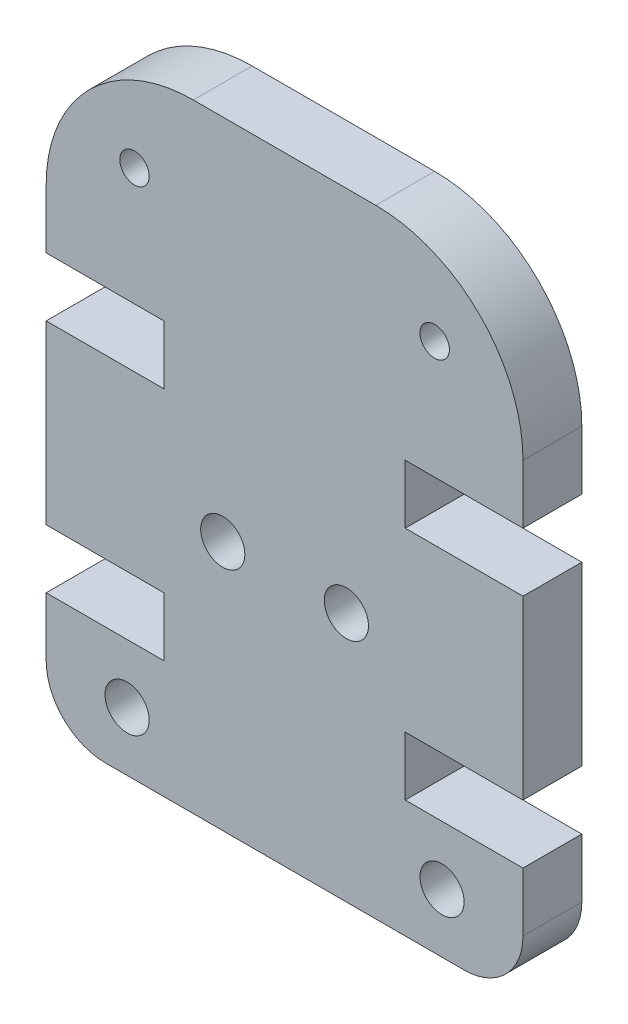
SolidWorks part; units mm, degrees
ref_plane "Front Plane" through (0, 0, 0) normal (0, 0, 1) x (1, 0, 0)
ref_plane "Top Plane" through (0, 0, 0) normal (0, 1, 0) x (1, 0, 0)
ref_plane "Right Plane" through (0, 0, 0) normal (1, 0, 0) x (0, 0, -1)
sketch "Sketch1" plane through (0, 0, 0) normal (0, 0, 1) x (1, 0, 0)
  line L12 (0, 16) -> (0, 14)
  line L13 (0, 12) -> (0, 6)
  line L14 (0, 14) -> (4, 14)
  line L15 (4, 12) -> (0, 12)
  line L16 (4, 14) -> (4, 12)
  line L17 (16.2, 12) -> (16.2, 6)
  line L18 (16.2, 16) -> (16.2, 14)
  line L19 (12.2, 14) -> (12.2, 12)
  line L20 (12.2, 12) -> (16.2, 12)
  line L21 (16.2, 14) -> (12.2, 14)
  line L22 (5, 21) -> (11.2, 21)
  line L23 (2, 0) -> (14.2, 0)
  line L24 (16.2, 2) -> (16.2, 4)
  line L25 (0, 2) -> (0, 4)
  line L26 (0, 6) -> (4, 6)
  line L27 (12.2, 4) -> (16.2, 4)
  line L28 (4, 6) -> (4, 4)
  line L29 (4, 4) -> (0, 4)
  line L30 (12.2, 6) -> (12.2, 4)
  line L31 (16.2, 6) -> (12.2, 6)
  circle A10 centre (10.2, 8.5) radius 0.75
  circle A11 centre (6, 8.5) radius 0.75
  arc A12 (14.2, 0) -> (16.2, 2) centre (14.2, 2) ccw
  arc A13 (5, 21) -> (0, 16) centre (5, 16) ccw
  arc A14 (16.2, 16) -> (11.2, 21) centre (11.2, 16) ccw
  circle A15 centre (3, 18) radius 0.5
  circle A16 centre (13.2, 18) radius 0.5
  arc A17 (0, 2) -> (2, 0) centre (2, 2) ccw
  circle A18 centre (13.45, 2) radius 0.75
  circle A19 centre (2.75, 2) radius 0.75
extrude "Boss-Extrude1" add sketch "Sketch1" along normal blind 2
